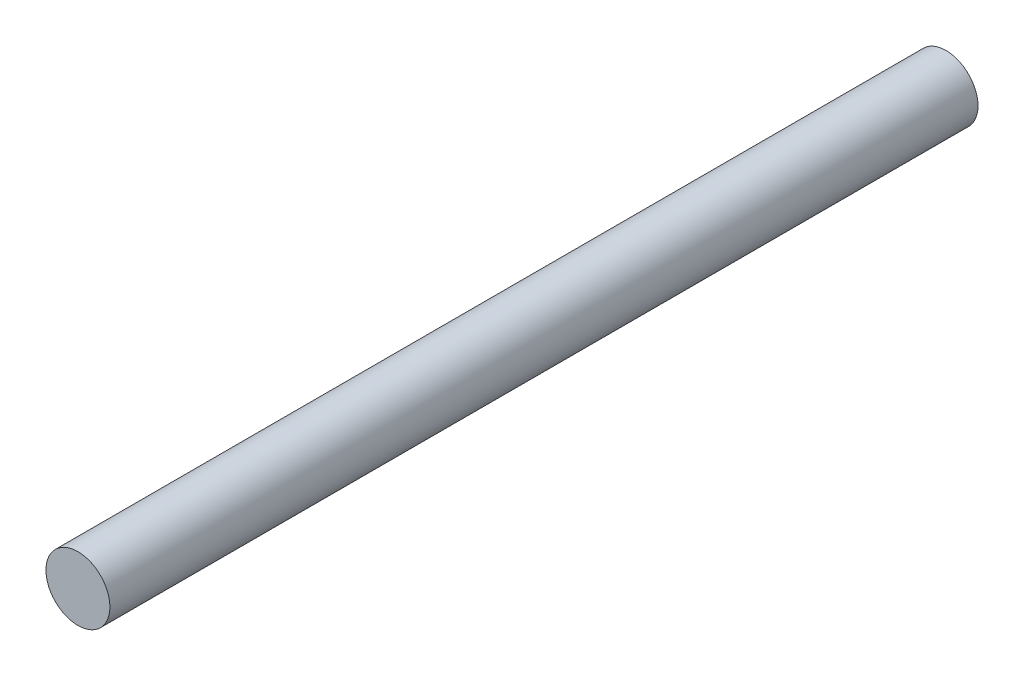
SolidWorks part; units mm, degrees
ref_plane "Plan de face" through (0, 0, 0) normal (0, 0, 1) x (1, 0, 0)
ref_plane "Plan de dessus" through (0, 0, 0) normal (0, 1, 0) x (1, 0, 0)
ref_plane "Plan de droite" through (0, 0, 0) normal (1, 0, 0) x (0, 0, -1)
sketch "Esquisse1" plane through (0, 0, 0) normal (0, 0, 1) x (1, 0, 0)
  circle A0 centre (0, 0) radius 3.5
  dimension "D1" = 7
extrude "Boss.-Extru.1" add sketch "Esquisse1" along normal blind 95
